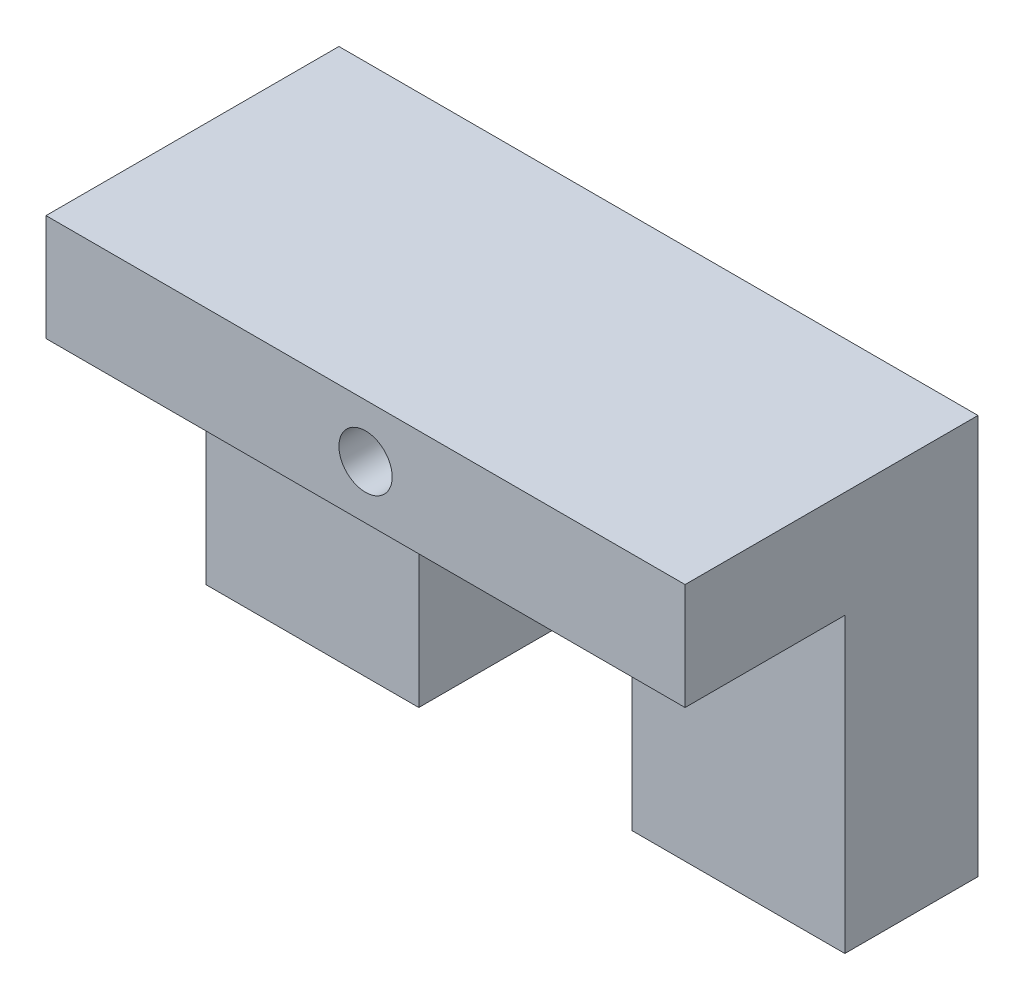
SolidWorks part; units mm, degrees
ref_plane "Спереди" through (0, 0, 0) normal (0, 0, 1) x (1, 0, 0)
ref_plane "Сверху" through (0, 0, 0) normal (0, 1, 0) x (1, 0, 0)
ref_plane "Справа" through (0, 0, 0) normal (1, 0, 0) x (0, 0, -1)
sketch "Эскиз1" plane through (0, 0, 0) normal (0, 0, 1) x (1, 0, 0)
  line L1 (0, 0) -> (120, 0)
  line L2 (0, 0) -> (0, -75)
  line L3 (0, -75) -> (120, -75)
  line L4 (120, 0) -> (120, -75)
  dimension "D1" = 75
  dimension "D2" = 120
extrude "Бобышка-Вытянуть1" add sketch "Эскиз1" along normal blind 25
sketch "Эскиз2" plane through (0, -75, 0) normal (0, -1, 0) x (1, 0, 0)
  line L0 (0, 25) -> (120, 25) construction
  line L1 (40, 25) -> (80, 25)
  line L2 (40, 25) -> (40, 0)
  line L3 (40, 0) -> (80, 0)
  line L4 (80, 25) -> (80, 0)
  line L5 (0, 0) -> (120, 0) construction
  dimension "D1" = 40
  dimension "D2" = 40
extrude "Вырез-Вытянуть1" cut sketch "Эскиз2" against normal blind 30
sketch "Эскиз3" plane through (0, 0, 25) normal (0, 0, 1) x (1, 0, 0)
  line L0 (0, -20) -> (120, -20)
  line L1 (0, 0) -> (0, -75) construction
  line L2 (120, -75) -> (120, 0) construction
  line L3 (0, -20) -> (0, 0)
  line L4 (0, 0) -> (120, 0)
  line L5 (120, 0) -> (120, -20)
  dimension "D1" = 20
extrude "Бобышка-Вытянуть2" add sketch "Эскиз3" along normal blind 30
sketch "Эскиз5" plane through (120, 0, 0) normal (1, 0, 0) x (0, 0, -1)
  line L0 (-55, -20) -> (-25, -45)
  line L2 (-25, -75) -> (-25, -20) construction
  line L3 (-25, -45) -> (-25, -20)
  line L4 (-25, -20) -> (-55, -20)
  dimension "D1" = 30
extrude "Бобышка-Вытянуть3" add sketch "Эскиз5" against normal blind 10 from offset 55 contours L4 L0 L3 offset against normal yes
sketch "Эскиз6" plane through (0, 0, 55) normal (0, 0, 1) x (1, 0, 0)
  line L0 (60, -45) -> (60, 0) construction
  line L1 (55, -45) -> (65, -45) construction
  line L2 (120, 0) -> (0, 0) construction
  line L3 (0, -10) -> (120, -10)
  line L4 (0, 0) -> (0, -20) construction
  line L5 (120, -20) -> (120, 0) construction
  circle A0 centre (60, -10) radius 5
  dimension "D1" = 10
extrude "Вырез-Вытянуть2" cut sketch "Эскиз6" against normal through all contours A0 L0 L3 | L0 A0 L3 | L0 L3 A0 | L3 L0 A0
